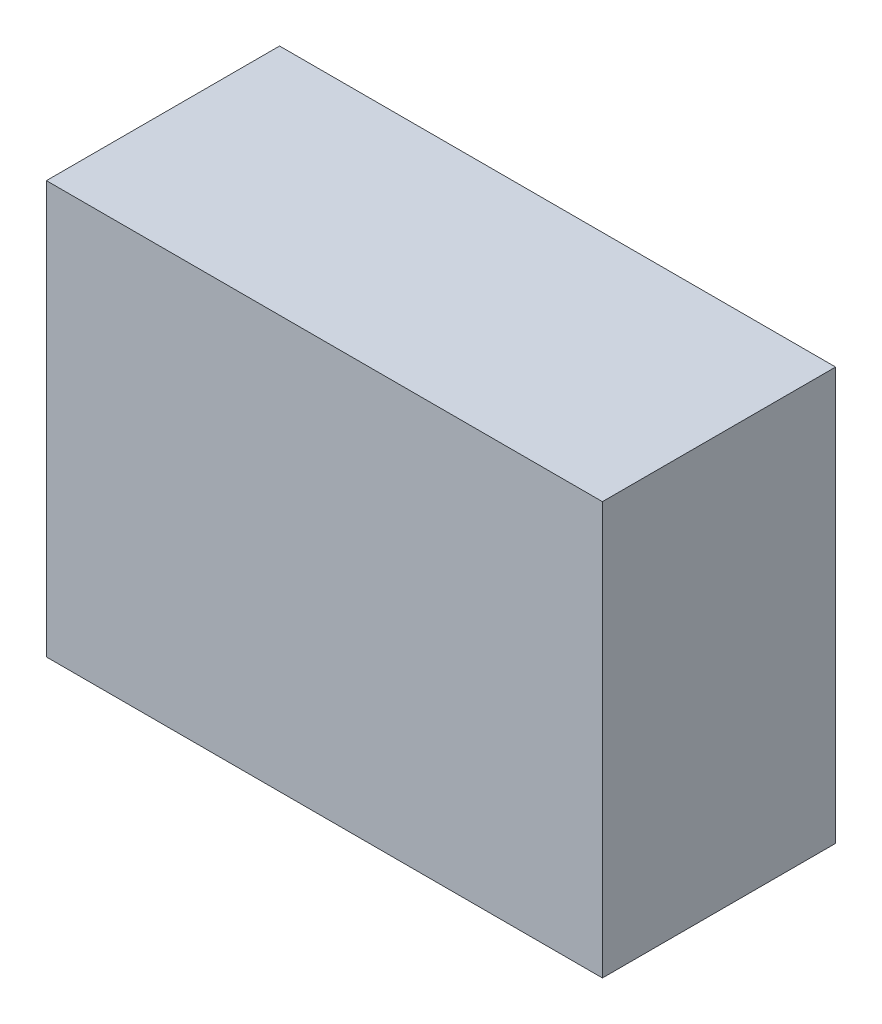
SolidWorks part; units mm, degrees
ref_plane "Plano frontal" through (0, 0, 0) normal (0, 0, 1) x (1, 0, 0)
ref_plane "Plano superior" through (0, 0, 0) normal (0, 1, 0) x (1, 0, 0)
ref_plane "Plano direito" through (0, 0, 0) normal (1, 0, 0) x (0, 0, -1)
sketch "Esboço1" plane through (0, 0, 0) normal (0, 0, 1) x (1, 0, 0)
  line L1 (-77.5, 57.5) -> (77.5, 57.5)
  line L2 (-77.5, 57.5) -> (-77.5, -57.5)
  line L3 (-77.5, -57.5) -> (77.5, -57.5)
  line L4 (77.5, 57.5) -> (77.5, -57.5)
  line L5 (-77.5, 57.5) -> (77.5, -57.5) construction
  line L6 (-77.5, -57.5) -> (77.5, 57.5) construction
  point P0 (0, 0)
  dimension "D1" = 115
  dimension "D2" = 155
extrude "Ressalto-extrusão1" add sketch "Esboço1" along normal blind 65
sketch "Esboço2" plane through (0, 0, 0) normal (0, 0, -1) x (-1, 0, 0)
  line L0 (-77.5, 57.5) -> (77.5, 57.5) construction
  line L1 (-74.5, 54.5) -> (74.5, 54.5)
  line L2 (-74.5, 54.5) -> (-74.5, -54.5)
  line L3 (-74.5, -54.5) -> (74.5, -54.5)
  line L4 (74.5, 54.5) -> (74.5, -54.5)
  line L5 (-74.5, 54.5) -> (74.5, -54.5) construction
  line L6 (-74.5, -54.5) -> (74.5, 54.5) construction
  line L7 (-77.5, -57.5) -> (-77.5, 57.5) construction
  point P0 (0, 0)
  dimension "D1" = 3
  dimension "D2" = 3
extrude "Corte-extrusão1" cut sketch "Esboço2" against normal blind 62
